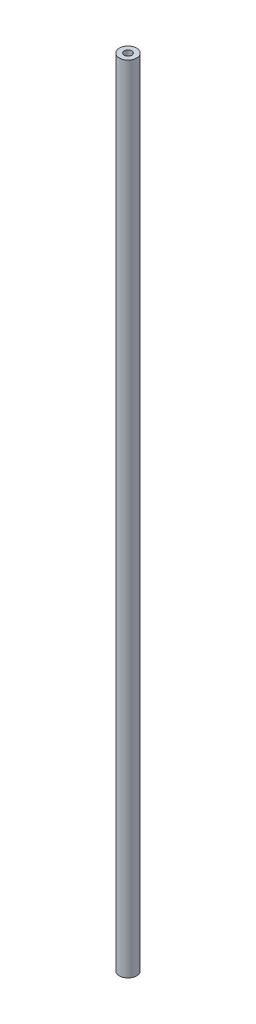
SolidWorks part; units mm, degrees
ref_plane "Front Plane" through (0, 0, 0) normal (0, 0, 1) x (1, 0, 0)
ref_plane "Top Plane" through (0, 0, 0) normal (0, 1, 0) x (1, 0, 0)
ref_plane "Right Plane" through (0, 0, 0) normal (1, 0, 0) x (0, 0, -1)
sketch "Sketch1" plane through (0, 0, 0) normal (0, 1, 0) x (1, 0, 0)
  circle A0 centre (0, 0) radius 0.25
  circle A1 centre (0, 0) radius 0.11
  dimension "D1" = 0.22
  dimension "D2" = 0.5
extrude "Boss-Extrude1" add sketch "Sketch1" along normal blind 23
